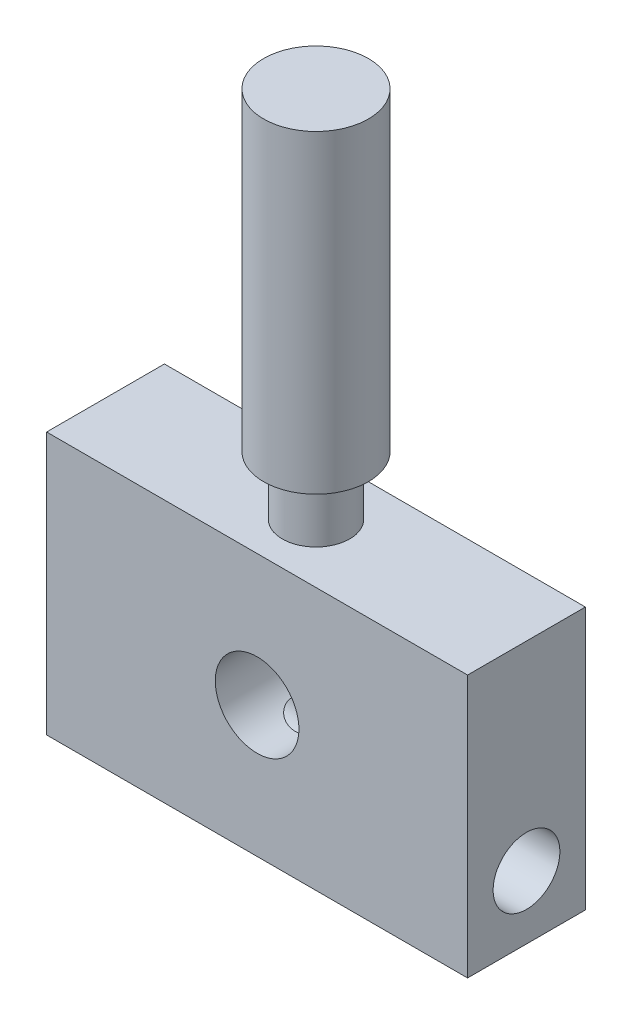
SolidWorks part; units mm, degrees
ref_plane "Front Plane" through (0, 0, 0) normal (0, 0, 1) x (1, 0, 0)
ref_plane "Top Plane" through (0, 0, 0) normal (0, 1, 0) x (1, 0, 0)
ref_plane "Right Plane" through (0, 0, 0) normal (1, 0, 0) x (0, 0, -1)
sketch "Sketch1" plane through (0, 0, 0) normal (0, 0, 1) x (1, 0, 0)
  line L1 (-53.5999, -33.4085) -> (53.5999, -33.4085)
  line L2 (-53.5999, -33.4085) -> (-53.5999, 33.4085)
  line L3 (-53.5999, 33.4085) -> (53.5999, 33.4085)
  line L4 (53.5999, -33.4085) -> (53.5999, 33.4085)
  line L5 (-53.5999, -33.4085) -> (53.5999, 33.4085) construction
  line L6 (-53.5999, 33.4085) -> (53.5999, -33.4085) construction
  point P0 (0, 0)
extrude "Boss-Extrude1" add sketch "Sketch1" along normal mid plane 30
sketch "Sketch2" plane through (0, 33.4085, 0) normal (0, 1, 0) x (1, 0, 0)
  circle A0 centre (0, 0) radius 8.5879
extrude "Boss-Extrude2" add sketch "Sketch2" along normal blind 15
sketch "Sketch3" plane through (0, 48.4085, 0) normal (0, 1, 0) x (1, 0, 0)
  circle A0 centre (0, 0) radius 13.3418
extrude "Boss-Extrude3" add sketch "Sketch3" along normal blind 80
sketch "Sketch4" plane through (-53.5999, 0, 0) normal (-1, 0, 0) x (0, 0, 1)
  circle A0 centre (0, -17.2854) radius 8.5
  dimension "D1" = 17
extrude "Cut-Extrude1" cut sketch "Sketch4" against normal blind 110
sketch "Sketch5" plane through (0, 0, -15) normal (0, 0, -1) x (-1, 0, 0)
  circle A0 centre (0, 0) radius 10.65
  dimension "D1" = 21.3
extrude "Cut-Extrude2" cut sketch "Sketch5" against normal blind 30
